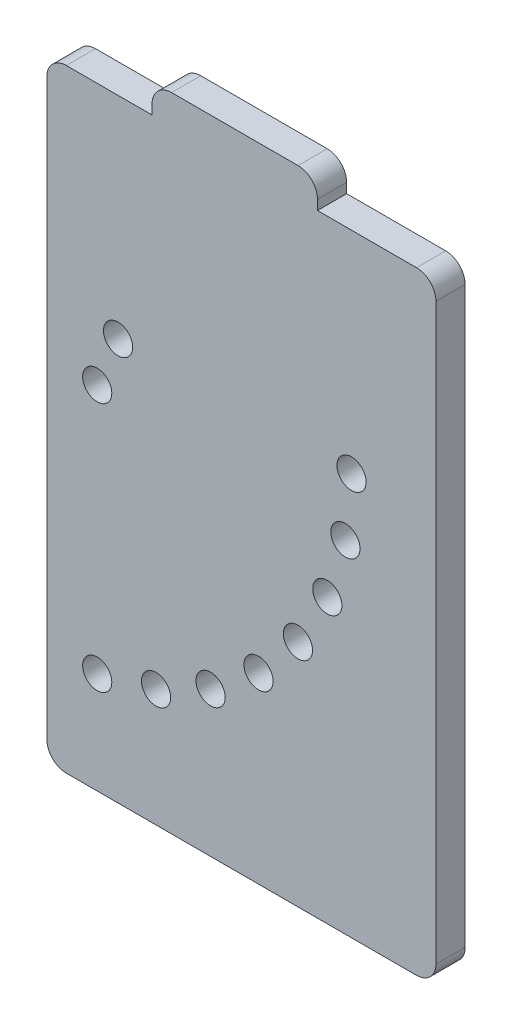
SolidWorks part; units mm, degrees
ref_plane "前视基准面" through (0, 0, 0) normal (0, 0, 1) x (1, 0, 0)
ref_plane "上视基准面" through (0, 0, 0) normal (0, 1, 0) x (1, 0, 0)
ref_plane "右视基准面" through (0, 0, 0) normal (1, 0, 0) x (0, 0, -1)
other "Configuration Table"
sketch "草图1" plane through (0, 0, 0) normal (0, 0, 1) x (1, 0, 0)
  line L0 (0, 34) -> (0, 22)
  line L5 (0, 10) -> (0, 22)
  line L6 (0, 10) -> (0, 7)
  line L7 (0, 34) -> (0, 37)
  line L9 (0, 41.32) -> (0, 37)
  line L10 (0, 41.32) -> (4.32, 41.32) construction
  line L11 (7.32, 41.32) -> (4.32, 41.32) construction
  line L12 (19.32, 41.32) -> (7.32, 41.32) construction
  line L13 (19.32, 41.32) -> (31.32, 41.32) construction
  line L14 (31.32, 41.32) -> (34.32, 41.32) construction
  line L15 (0, 7) -> (0, 0)
  line L20 (4.32, 41.32) -> (4.32, 63)
  line L21 (4.32, 63) -> (34.32, 63)
  line L22 (34.32, 63) -> (34.32, 41.32)
  line L23 (0, 41.32) -> (5.176, 36.144) construction
  line L24 (5.176, 36.144) -> (5.176, 10.4307) construction
  line L25 (0, 0) -> (40, 0)
  line L30 (40, 0) -> (40, 63)
  line L31 (40, 63) -> (34.32, 63)
  line L32 (4.32, 63) -> (0, 63)
  line L33 (0, 63) -> (0, 41.32)
  line L34 (10.82, 63) -> (10.82, 66)
  line L35 (10.82, 66) -> (27.82, 66)
  line L36 (27.82, 66) -> (27.82, 63)
  line L37 (19.32, 66) -> (19.32, 63) construction
  line L41 (19.32, 41.32) -> (19.32, 0) construction
  arc A0 (0, 34) -> (7.32, 41.32) centre (0, 41.32) ccw construction
  arc A1 (0, 22) -> (19.32, 41.32) centre (0, 41.32) ccw construction
  arc A2 (0, 10) -> (31.32, 41.32) centre (0, 41.32) ccw construction
  arc A3 (0, 37) -> (4.32, 41.32) centre (0, 41.32) ccw
  arc A4 (0, 7) -> (34.32, 41.32) centre (0, 41.32) ccw
  circle A6 centre (5.176, 36.144) radius 1.5
  circle A7 centre (7.32, 41.32) radius 1.5
  circle A8 centre (31.32, 41.32) radius 1.5
  circle A9 centre (30.6914, 35.0768) radius 1.5
  circle A10 centre (28.831, 29.0841) radius 1.5
  circle A11 centre (25.8133, 23.5826) radius 1.5
  circle A12 centre (21.7595, 18.793) radius 1.5
  circle A13 centre (16.8323, 14.9076) radius 1.5
  circle A14 centre (11.2295, 12.0824) radius 1.5
  circle A15 centre (5.176, 10.4307) radius 1.5
  point P49 (40, 44.101)
  point P52 (40, 44.4163)
  point P53 (40, 9.1601)
  dimension "D7" = 3
  dimension "D1" = 3
  dimension "D2" = 24
  dimension "D3" = 19.32
  dimension "D4" = 22
  dimension "D5" = 63
  dimension "D6" = 45
  dimension "D8" = 8
  dimension "D9" = 40
  dimension "D10" = 17
  dimension "D11" = 3
extrude "凸台-拉伸1" add sketch "草图1" along normal blind 3
fillet "圆角1" radius 2 4 edges at (0, 63, 1.5) (40, 63, 1.5) (0, 0, 1.5) (40, 0, 1.5)
fillet "圆角2" radius 2 2 edges at (27.82, 66, 1.5) (10.82, 66, 1.5)
